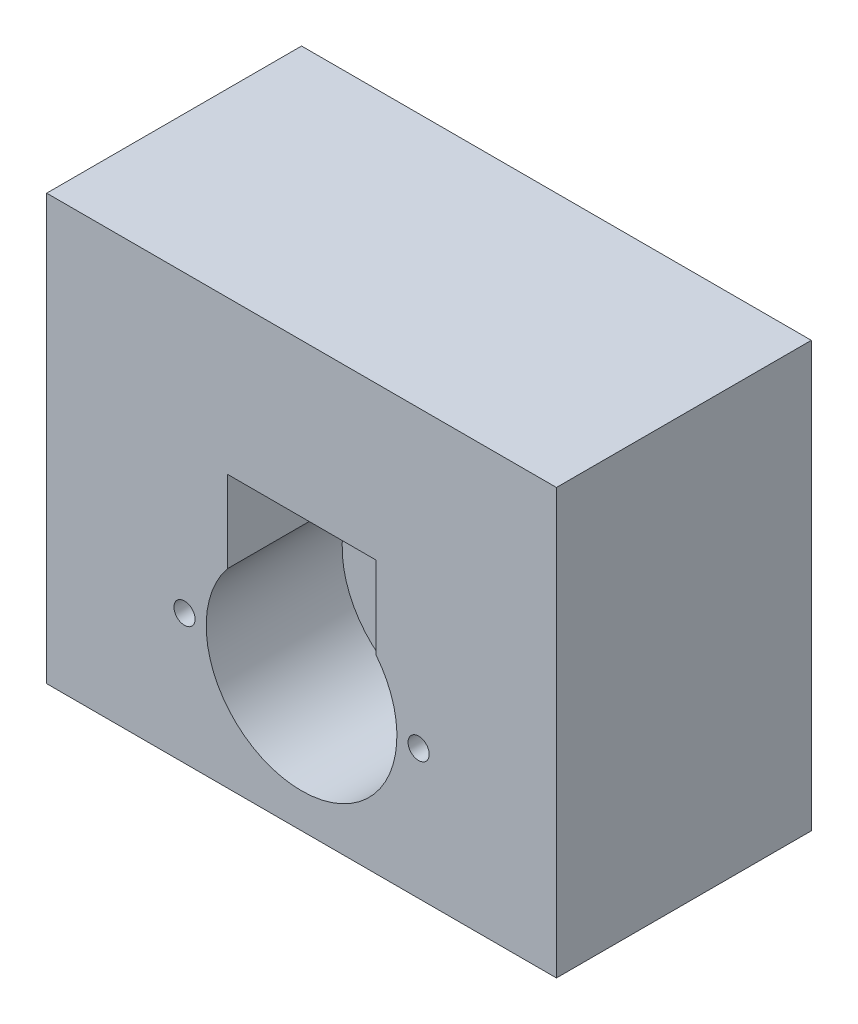
SolidWorks part; units mm, degrees
ref_plane "Front Plane" through (0, 0, 0) normal (0, 0, 1) x (1, 0, 0)
ref_plane "Top Plane" through (0, 0, 0) normal (0, 1, 0) x (1, 0, 0)
ref_plane "Right Plane" through (0, 0, 0) normal (1, 0, 0) x (0, 0, -1)
sketch "Sketch1" plane through (0, 0, 0) normal (0, 0, 1) x (1, 0, 0)
  line L1 (38.1, -31.75) -> (-38.1, -31.75)
  line L2 (38.1, -31.75) -> (38.1, 31.75)
  line L3 (38.1, 31.75) -> (-38.1, 31.75)
  line L4 (-38.1, -31.75) -> (-38.1, 31.75)
  line L5 (38.1, -31.75) -> (-38.1, 31.75) construction
  line L6 (38.1, 31.75) -> (-38.1, -31.75) construction
  point P0 (0, 0)
  dimension "D1" = 63.5
  dimension "D2" = 76.2
extrude "Boss-Extrude1" add sketch "Sketch1" along normal blind 38.1 separate body
sketch "Sketch5" plane through (0, 0, 38.1) normal (0, 0, 1) x (1, 0, 0)
  line L0 (-38.1, -31.75) -> (38.1, -31.75) construction
  line L5 (38.1, -31.75) -> (38.1, 31.75) construction
  line L14 (0, 8.8784) -> (0, -12.3156) construction
  line L16 (-11.0954, -3.3675) -> (-11.0954, 8.8709)
  line L17 (11.0954, -3.3675) -> (11.0954, 8.8709)
  line L18 (-11.0954, 8.8709) -> (11.0954, 8.8709)
  arc A1 (-11.0954, -3.3675) -> (11.0954, -3.3675) centre (0, -12.3156) ccw
  dimension "D2" = 19.4344
  dimension "D3" = 38.1
extrude "Cut-Extrude2" cut sketch "Sketch5" against normal blind 20.32
sketch "Sketch6" plane through (0, 0, 38.1) normal (0, 0, 1) x (1, 0, 0)
  line L4 (-38.1, 31.75) -> (-38.1, -31.75)
  line L5 (-38.1, -31.75) -> (38.1, -31.75)
  line L6 (38.1, -31.75) -> (38.1, 31.75)
  line L7 (38.1, 31.75) -> (-38.1, 31.75)
  line L8 (-38.1, 31.75) -> (-38.1, -31.75)
  line L9 (-38.1, -31.75) -> (38.1, -31.75)
  line L10 (38.1, -31.75) -> (38.1, 31.75)
  line L11 (38.1, 31.75) -> (-38.1, 31.75)
  circle A0 centre (17.5, -12.3156) radius 2.25 construction
  circle A1 centre (-17.5, -12.3156) radius 2.25 construction
  circle A2 centre (17.5, -12.3156) radius 2.25
  circle A3 centre (-17.5, -12.3156) radius 2.25
  circle A4 centre (17.5, -12.3156) radius 1.58
  circle A5 centre (-17.5, -12.3156) radius 1.58
  dimension "D2" = 3.16
  dimension "D3" = 3.16
  dimension "D1" = 0
extrude "Cut-Extrude3" cut sketch "Sketch6" against normal blind 20.32 contours A4 | A5
